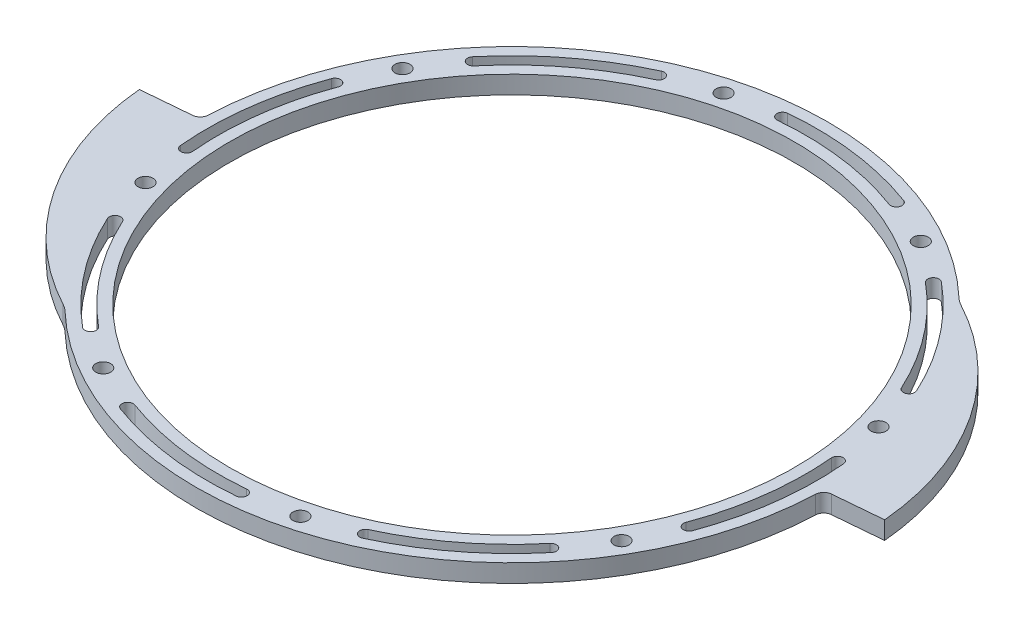
SolidWorks part; units mm, degrees
material "Alloy Steel"
ref_plane "Front Plane" through (0, 0, 0) normal (0, 0, 1) x (1, 0, 0)
ref_plane "Top Plane" through (0, 0, 0) normal (0, 1, 0) x (1, 0, 0)
ref_plane "Right Plane" through (0, 0, 0) normal (1, 0, 0) x (0, 0, -1)
sketch "Sketch1" plane through (0, 0, 0) normal (0, 1, 0) x (1, 0, 0)
  line L0 (0, 0) -> (-132, 0) construction
  line L1 (-132.0082, 0.0941) -> (-134.7743, 31.7103) construction
  line L2 (-111.9863, 1.751) -> (-132, 0)
  line L3 (-132, 0) -> (-132, 32.0934) construction
  line L4 (-129.3938, 0) -> (-182.8754, 0) construction
  line L5 (-112, 0) -> (-132, 0) construction
  line L6 (-79.4774, -79.4774) -> (0, 0) construction
  circle A0 centre (0, 0) radius 100
  arc A10 (-132, 0) -> (-79.4774, -79.4774) centre (-32.4231, 8.7118) ccw
  arc A11 (-79.4774, -79.4774) -> (-77.2845, -81.0624) centre (-84.1849, -88.3001) cw
  arc A12 (-77.2845, -81.0624) -> (-111.9863, 1.751) centre (0, 0) ccw
  dimension "D1" = 200
  dimension "D6" = 10
  dimension "D4" = 5
  dimension "D7" = 45
  dimension "D2" = 12
  dimension "D3" = 5
  dimension "D5" = 20
extrude "Boss-Extrude1" add sketch "Sketch1" along normal mid plane 6.35
fillet "Fillet1" radius 3 1 edges at (-111.9863, 0, -1.751)
pattern_circular "CirPattern1" count 2 over 360 about axis through (0, 0, 0) along (0, 1, 0) of "Boss-Extrude1", "Fillet1"
sketch "Sketch2" plane through (0, 3.175, 0) normal (0, 1, 0) x (1, 0, 0)
  line L0 (-102.3881, -27.4348) -> (0, 0) construction
  line L1 (0, 0) -> (-106, 0) construction
  circle A0 centre (-102.3881, -27.4348) radius 2.65
  circle A2 centre (0, 0) radius 106 construction
  circle A3 centre (0, 0) radius 100 construction
  dimension "D3" = 5.3
  dimension "D1" = 106
  dimension "D2" = 6
  dimension "D4" = 15
extrude "Cut-Extrude1" cut sketch "Sketch2" against normal through all
pattern_circular "CirPattern2" count 8 over 360 about axis through (0, 0, 0) along (0, 1, 0) of "Cut-Extrude1"
sketch "Sketch3" plane through (0, 3.175, 0) normal (0, 1, 0) x (1, 0, 0)
  line L0 (-102.3881, -27.4348) -> (0, 0) construction
  line L1 (-102.3881, -27.4348) -> (0, 0) construction
  line L2 (0, 0) -> (-91.7987, 53) construction
  line L3 (-105.0932, 13.8358) -> (0, 0) construction
  arc A0 (-105.5538, -9.7154) -> (-99.4426, 36.7037) centre (0, 0) cw construction
  circle A1 centre (0, 0) radius 106 construction
  arc A2 (-101.3189, 37.3962) -> (-107.5454, -9.8987) centre (0, 0) ccw
  arc A3 (-97.5664, 36.0112) -> (-103.5622, -9.5321) centre (0, 0) ccw
  arc A4 (-97.5664, 36.0112) -> (-101.3189, 37.3962) centre (-99.4426, 36.7037) ccw
  arc A5 (-107.5454, -9.8987) -> (-103.5622, -9.5321) centre (-105.5538, -9.7154) ccw
  point P3 (-105.0932, 13.8358)
  dimension "D4" = 2
  dimension "D1" = 45
  dimension "D2" = 22.5
  dimension "D3" = 18
extrude "Lightening Cut" cut sketch "Sketch3" against normal through all
pattern_circular "Lightening Pattern" count 8 over 360 about axis through (0, 0, 0) along (0, 1, 0) of "Lightening Cut"
equation "\"ring_id\"=200"
equation "\"D1@Sketch1\"=\"ring_id\""
equation "\"D2@Sketch2\"=\"D2@Sketch1\"/2"
equation "\"D2@Sketch3\"=\"D1@Sketch3\"/2"
